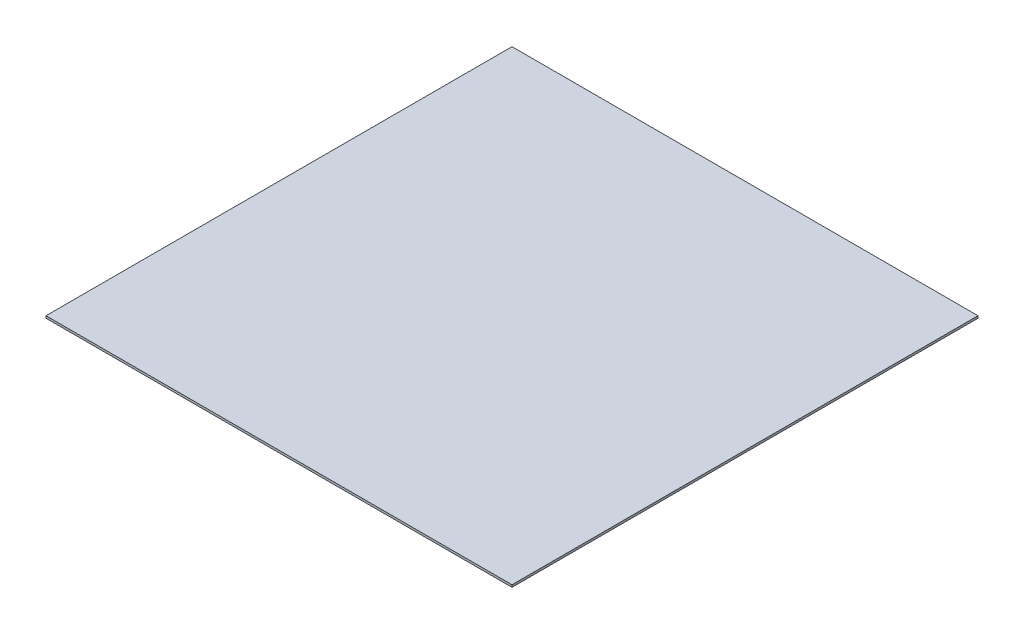
SolidWorks part; units mm, degrees
material "6061-T6 (SS)"
ref_plane "Front Plane" through (0, 0, 0) normal (0, 0, 1) x (1, 0, 0)
ref_plane "Top Plane" through (0, 0, 0) normal (0, 1, 0) x (1, 0, 0)
ref_plane "Right Plane" through (0, 0, 0) normal (1, 0, 0) x (0, 0, -1)
sketch "Sketch1" plane through (0, 0, 0) normal (0, 1, 0) x (1, 0, 0)
  line L1 (0, 0) -> (2000, 0)
  line L2 (0, 0) -> (0, -2000)
  line L3 (0, -2000) -> (2000, -2000)
  line L4 (2000, 0) -> (2000, -2000)
  dimension "D1" = 2000
  dimension "D2" = 2000
extrude "Boss-Extrude1" add sketch "Sketch1" along normal blind 9.525
